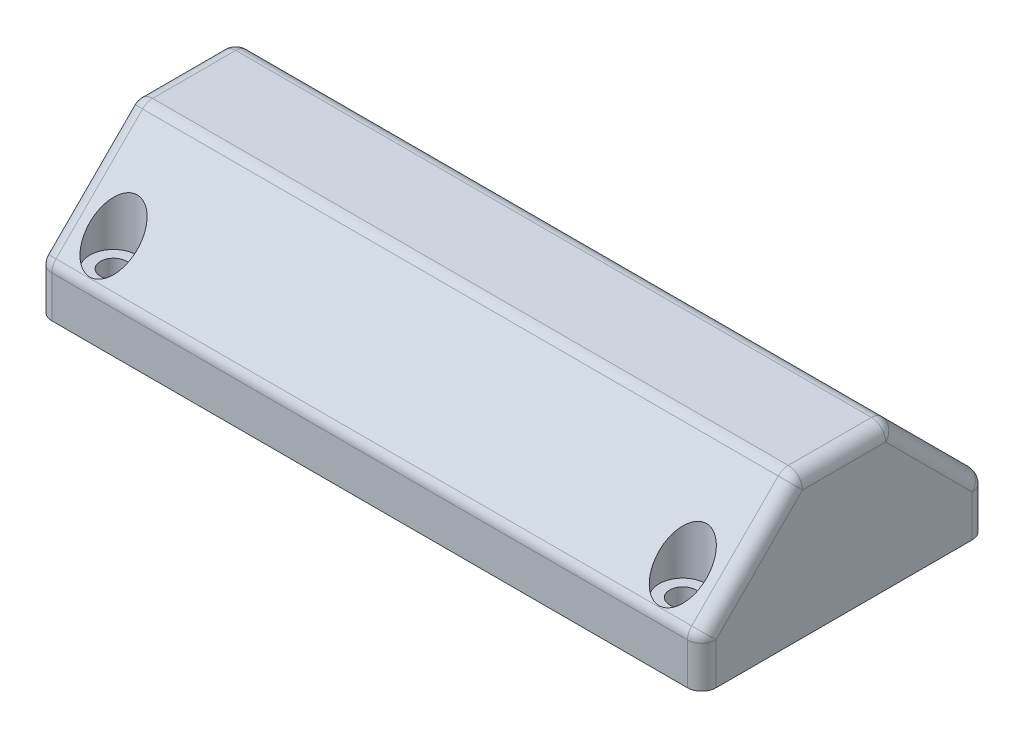
SolidWorks part; units mm, degrees
ref_plane "Front Plane" through (0, 0, 0) normal (0, 0, 1) x (1, 0, 0)
ref_plane "Top Plane" through (0, 0, 0) normal (0, 1, 0) x (1, 0, 0)
ref_plane "Right Plane" through (0, 0, 0) normal (1, 0, 0) x (0, 0, -1)
sketch "Sketch1" plane through (0, 0, 0) normal (0, 1, 0) x (1, 0, 0)
  line L0 (65, -19) -> (65, 19) construction
  line L1 (-65, -19) -> (65, -19) construction
  line L2 (-65, 19) -> (-65, -19) construction
  line L3 (65, 19) -> (-65, 19) construction
  line L4 (67, 30) -> (-67, 30)
  line L5 (-70, 27) -> (-70, -27)
  line L6 (-67, -30) -> (67, -30)
  line L7 (70, -27) -> (70, 27)
  line L8 (67, 30) -> (-67, 30)
  line L9 (-70, 27) -> (-70, -27)
  line L10 (-67, -30) -> (67, -30)
  line L11 (70, -27) -> (70, 27)
  line L12 (65, -19) -> (65, 19)
  line L13 (-65, -19) -> (65, -19)
  line L14 (-65, 19) -> (-65, -19)
  line L15 (65, 19) -> (-65, 19)
  line L17 (70, 30) -> (-70, 30)
  line L18 (70, 30) -> (70, -30)
  line L19 (70, -30) -> (-70, -30)
  line L20 (-70, 30) -> (-70, -30)
  circle A0 centre (-60, 24) radius 2.75 construction
  circle A1 centre (-60, -24) radius 2.75 construction
  circle A2 centre (60, -24) radius 2.75 construction
  circle A3 centre (60, 24) radius 2.75 construction
  arc A4 (-67, 30) -> (-70, 27) centre (-67, 27) ccw
  arc A5 (-70, -27) -> (-67, -30) centre (-67, -27) ccw
  arc A6 (67, -30) -> (70, -27) centre (67, -27) ccw
  arc A7 (70, 27) -> (67, 30) centre (67, 27) ccw
  arc A8 (-67, 30) -> (-70, 27) centre (-67, 27) ccw
  arc A9 (-70, -27) -> (-67, -30) centre (-67, -27) ccw
  arc A10 (67, -30) -> (70, -27) centre (67, -27) ccw
  arc A11 (70, 27) -> (67, 30) centre (67, 27) ccw
  circle A12 centre (-60, 24) radius 2.75
  circle A13 centre (-60, -24) radius 2.75
  circle A14 centre (60, -24) radius 2.75
  circle A15 centre (60, 24) radius 2.75
  point P32 (0, 0)
  point P33 (84.421, 39.0562)
  circle M13 centre (-60, 24) radius 2.75
  line M14 (67, 30) -> (-67, 30)
  arc M15 (-67, 30) -> (-70, 27) centre (-67, 27) ccw
  line M16 (-70, 27) -> (-70, -27)
  arc M17 (-70, -27) -> (-67, -30) centre (-67, -27) ccw
  line M18 (-67, -30) -> (67, -30)
  arc M19 (67, -30) -> (70, -27) centre (67, -27) ccw
  line M20 (70, -27) -> (70, 27)
  arc M21 (70, 27) -> (67, 30) centre (67, 27) ccw
  line M22 (-65, -19) -> (-65, 19)
  line M23 (-65, 19) -> (65, 19)
  line M24 (65, 19) -> (65, -19)
  line M25 (65, -19) -> (-65, -19)
  circle M26 centre (60, -24) radius 2.75
  circle M27 centre (-60, -24) radius 2.75
  circle M28 centre (60, 24) radius 2.75
  dimension "D1" = 0
extrude "Boss-Extrude1" add sketch "Sketch1" along normal blind 10 contours L18 L17 M21 | M21 M14 M15 M16 M17 M18 M19 M20 M27 M28 M26 M25 M22 M23 M24 M13 | L19 L18 M19 | L17 L20 M15 | L20 L19 M17 | M22 M25 M24 M23
sketch "Sketch3" plane through (0, 10, 0) normal (0, 1, 0) x (1, 0, 0)
  circle A0 centre (60, 24) radius 5
  circle A1 centre (60, -24) radius 5
  circle A2 centre (-60, 24) radius 5
  circle A3 centre (-60, -24) radius 5
  dimension "D1" = 10
sketch "Sketch2" plane through (-70, 0, 0) normal (-1, 0, 0) x (0, 0, 1)
  line L0 (-30, 10) -> (30, 10) construction
  line L1 (10, 30) -> (-10, 30)
  line L2 (10, 30) -> (10, 10)
  line L3 (10, 10) -> (-10, 10)
  line L4 (-10, 30) -> (-10, 10)
  line L5 (10, 30) -> (-10, 10) construction
  line L6 (10, 10) -> (-10, 30) construction
  line L7 (-30, 10) -> (-10, 30)
  line L8 (10, 30) -> (30, 10)
  line L9 (30, 10) -> (30, 0) construction
  line L10 (-30, 0) -> (30, 0) construction
  point P0 (0, 20)
  point P8 (1.0551, 19.1212)
  point P13 (30, 10)
  point P14 (13.0345, 36.6069)
  point P17 (0, 0)
  point P18 (-13.4802, 27.7594)
  point P19 (10, 30)
  point P20 (30, 32.3869)
  point P21 (30, 10)
  point P22 (30, 14.6685)
  line M7 (30, 10) -> (-30, 10)
  dimension "D1" = 20
  dimension "D2" = 20
extrude "Boss-Extrude3" add sketch "Sketch2" against normal through all contours L7 L4 M7 | L1 L4 L2 M7 | L8 L2 M7
extrude "Cut-Extrude1" cut sketch "Sketch3" along normal through all
fillet "Fillet1" radius 3 14 edges at (0, 10, -30) (70, 5, 30) (-70, 5, 30) (-70, 5, -30) (70, 5, -30) (0, 10, 30) (-70, 20, -20) (70, 30, 0) (0, 30, -10) (-70, 20, 20) (0, 30, 10) (70, 20, -20) (70, 20, 20) (-70, 30, 0)
